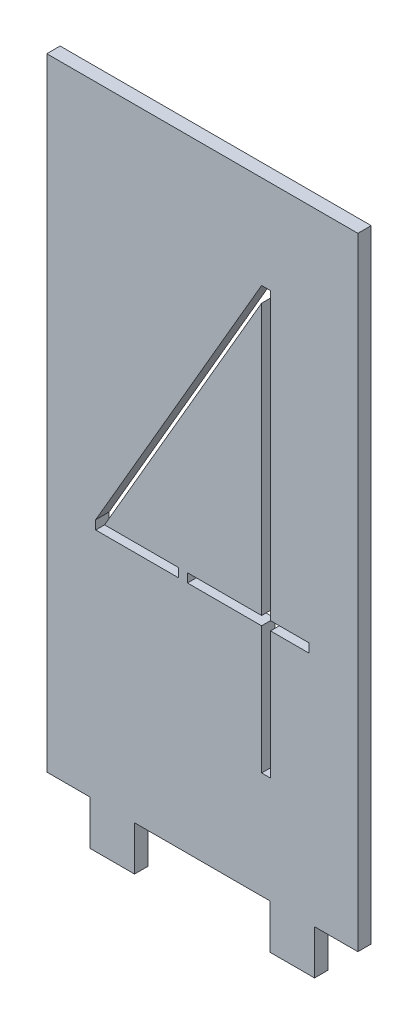
SolidWorks part; units mm, degrees
material "Glas"
ref_plane "Ebene vorne" through (0, 0, 0) normal (0, 0, 1) x (1, 0, 0)
ref_plane "Ebene oben" through (0, 0, 0) normal (0, 1, 0) x (1, 0, 0)
ref_plane "Ebene rechts" through (0, 0, 0) normal (1, 0, 0) x (0, 0, -1)
sketch "Skizze1" plane through (0, 0, 0) normal (0, 0, 1) x (1, 0, 0)
  line L1 (0, 0) -> (35, 0)
  line L2 (0, 0) -> (0, 75)
  line L3 (0, 75) -> (35, 75)
  line L4 (35, 0) -> (35, 75)
  dimension "D1" = 35
  dimension "D2" = 75
extrude "Aufsatz-Linear austragen1" add sketch "Skizze1" along normal blind 1.5
sketch "Skizze3" plane through (0, 0, 1.5) normal (0, 0, 1) x (1, 0, 0)
  line L0 (0, 0) -> (35, 0) construction
  line L1 (9.875, 0) -> (25.125, 0)
  line L2 (9.875, 0) -> (9.875, 5)
  line L3 (9.875, 5) -> (25.125, 5)
  line L4 (25.125, 0) -> (25.125, 5)
  line L5 (35, 0) -> (35, 75) construction
  line L6 (30.125, 5) -> (35, 5)
  line L7 (30.125, 5) -> (30.125, 0)
  line L8 (30.125, 0) -> (35, 0)
  line L9 (35, 5) -> (35, 0)
  line L10 (4.875, 5) -> (0, 5)
  line L11 (4.875, 5) -> (4.875, 0)
  line L12 (4.875, 0) -> (0, 0)
  line L13 (0, 5) -> (0, 0)
  dimension "D1" = 4.875
  dimension "D2" = 4.875
  dimension "D3" = 0
  dimension "D4" = 5
  dimension "D5" = 5
  dimension "D6" = 5
  dimension "D7" = 5
extrude "Schnitt-Linear austragen12" cut sketch "Skizze3" against normal blind 20
sketch "Skizze8" plane through (0, 0, 1.5) normal (0, 0, 1) x (1, 0, 0)
  line L0 (5.5, 32.3422) -> (24.1675, 64.5)
  line L2 (5.5, 32.3422) -> (5.5, 31.3422)
  line L4 (29.5, 32.3422) -> (29.5, 31.3422)
  line L7 (24.1675, 64.5) -> (25.1675, 64.5)
  line L8 (25.1675, 17) -> (25.1675, 31.3422)
  line L9 (25.1675, 17) -> (24.1675, 17)
  line L10 (25.1675, 32.3422) -> (25.1675, 64.5)
  line L11 (35, 5) -> (35, 75) construction
  line L12 (0, 75) -> (0, 5) construction
  line L13 (35, 75) -> (0, 75) construction
  line L14 (25.125, 5) -> (9.875, 5) construction
  line L15 (6.5, 32.3422) -> (24.1675, 32.3422)
  line L16 (29.5, 32.3422) -> (25.1675, 32.3422)
  line L17 (5.5, 31.3422) -> (24.1675, 31.3422)
  line L18 (25.1675, 31.3422) -> (29.5, 31.3422)
  line L19 (24.1675, 17) -> (24.1675, 31.3422)
  line L20 (24.1675, 32.3422) -> (24.1675, 62.7773)
  line L21 (6.5, 32.3422) -> (24.1675, 62.7773)
  point P13 (24.6675, 64.5)
  dimension "D3" = 5.5
  dimension "D4" = 5.5
  dimension "D5" = 10.5
  dimension "D6" = 12
extrude "Schnitt-Linear austragen15" cut sketch "Skizze8" against normal blind 1.5
sketch "Skizze9" plane through (0, 0, 1.5) normal (0, 0, 1) x (1, 0, 0)
  line L0 (24.1675, 32.3422) -> (24.1675, 62.7773) construction
  line L1 (14.8275, 34.233) -> (15.8275, 34.233)
  line L2 (14.8275, 34.233) -> (14.8275, 28.4367)
  line L3 (14.8275, 28.4367) -> (15.8275, 28.4367)
  line L4 (15.8275, 34.233) -> (15.8275, 28.4367)
  dimension "D1" = 1
  dimension "D2" = 8.34
extrude "Aufsatz-Linear austragen6" add sketch "Skizze9" against normal blind 1.5
